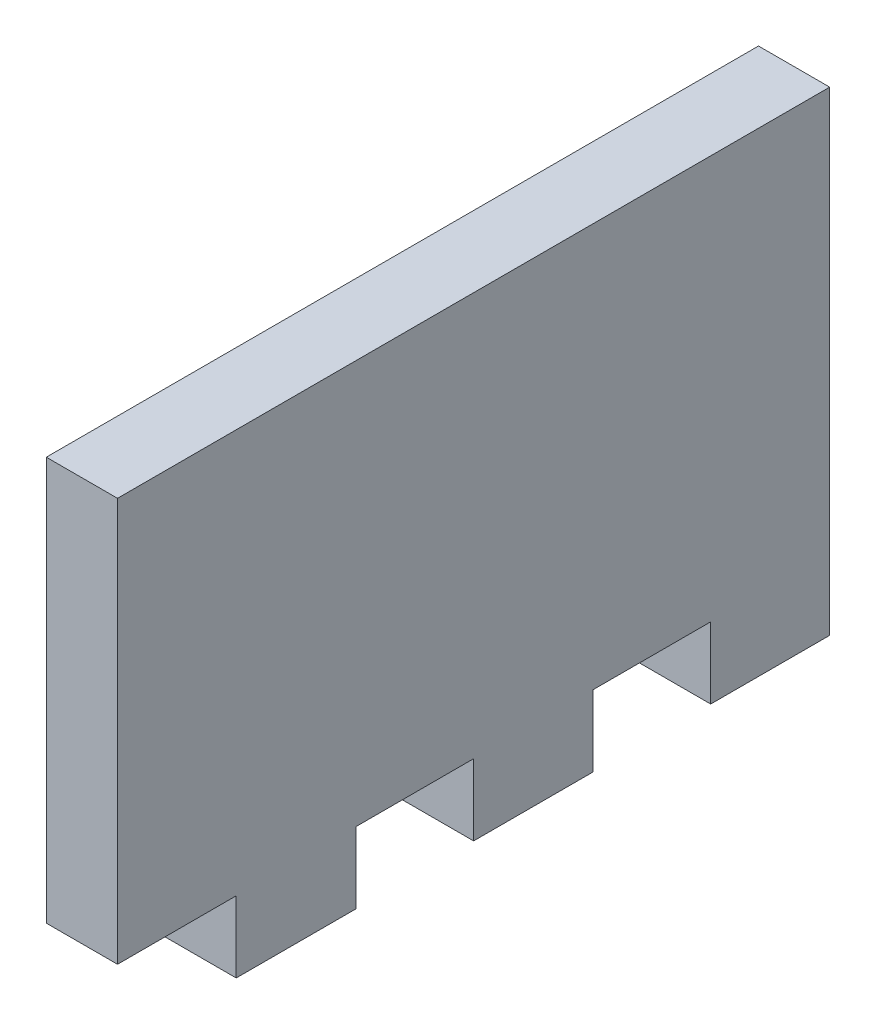
SolidWorks part; units mm, degrees
ref_plane "Front Plane" through (0, 0, 0) normal (0, 0, 1) x (1, 0, 0)
ref_plane "Top Plane" through (0, 0, 0) normal (0, 1, 0) x (1, 0, 0)
ref_plane "Right Plane" through (0, 0, 0) normal (1, 0, 0) x (0, 0, -1)
sketch "Sketch2" plane through (0, 0, 0) normal (1, 0, 0) x (0, 0, -1)
  line L0 (30, 20) -> (30, 14.9645)
  line L1 (0, 0) -> (30, 0)
  line L2 (0, 0) -> (0, 20)
  line L3 (0, 20) -> (30, 20)
  line L4 (30, 0) -> (30, 20)
  line L8 (30, 10) -> (30, 5.0429)
  point P9 (0, 0)
  dimension "D1" = 30
  dimension "D2" = 20
extrude "Boss-Extrude2" add sketch "Sketch2" along normal blind 3 contours L2 L1 L4 L3
sketch "Sketch4" plane through (3, 0, 0) normal (1, 0, 0) x (0, 0, -1)
  line L2 (0, 0) -> (5, 0)
  line L3 (0, 0) -> (0, 3)
  line L4 (0, 3) -> (5, 3)
  line L5 (5, 0) -> (5, 3)
  line L14 (10.0397, 0) -> (15, 0)
  line L15 (10.0397, 0) -> (10.0397, 3)
  line L16 (10.0397, 3) -> (15, 3)
  line L17 (15, 0) -> (15, 3)
  line L21 (20.0355, 0) -> (24.9871, 0)
  line L22 (20.0355, 0) -> (20.0355, 3)
  line L23 (20.0355, 3) -> (24.9871, 3)
  line L24 (24.9871, 0) -> (24.9871, 3)
  line M27 (0, 20) -> (0, 0)
  line M28 (0, 0) -> (30, 0)
  dimension "D1" = 5
  dimension "D2" = 3
extrude "Cut-Extrude1" cut sketch "Sketch4" against normal blind 3 contours L5 L4 M28 M27 | L17 L16 L15 M28 | L24 L23 L22 M28
